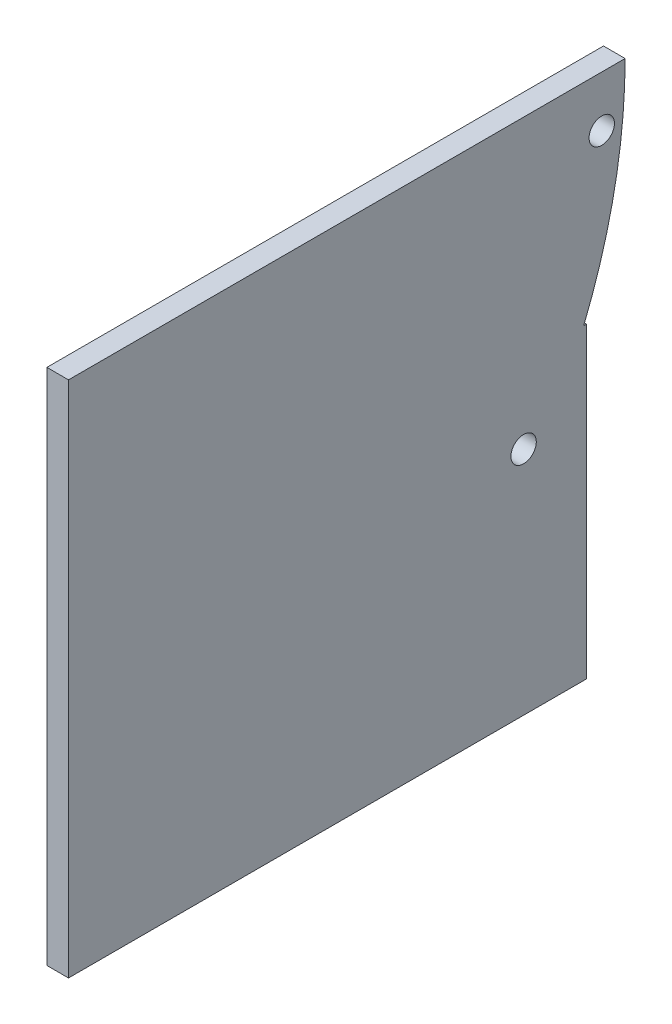
SolidWorks part; units mm, degrees
ref_plane "Front Plane" through (0, 0, 0) normal (0, 0, 1) x (1, 0, 0)
ref_plane "Top Plane" through (0, 0, 0) normal (0, 1, 0) x (1, 0, 0)
ref_plane "Right Plane" through (0, 0, 0) normal (1, 0, 0) x (0, 0, -1)
sketch "Sketch1" plane through (0, 0, 0) normal (1, 0, 0) x (0, 0, -1)
  line L0 (0, 0) -> (0, -139.192)
  line L1 (0, 0) -> (139.192, 0)
  line L2 (0, 0) -> (113.8047, -71.9099)
  line L3 (0, -129.54) -> (91.3565, -129.54)
  line L5 (129.54, 0) -> (139.192, 0)
  line L6 (0, -129.54) -> (129.54, -129.54)
  line L7 (0, -129.54) -> (0, -52.6814)
  line L8 (0, -52.6814) -> (129.54, -52.6814)
  line L9 (129.54, -129.54) -> (129.54, -52.6814)
  circle A0 centre (0, 0) radius 129.54
  circle A1 centre (0, 0) radius 139.192
  circle A2 centre (133.35, -12.7) radius 3.175
  circle A3 centre (113.8047, -71.9099) radius 3.175
  dimension "D1" = 9.652
  dimension "D4" = 134.62
  dimension "D2" = 12.7
  dimension "D3" = 133.35
extrude "Boss-Extrude2" add sketch "Sketch1" along normal blind 5.4102
